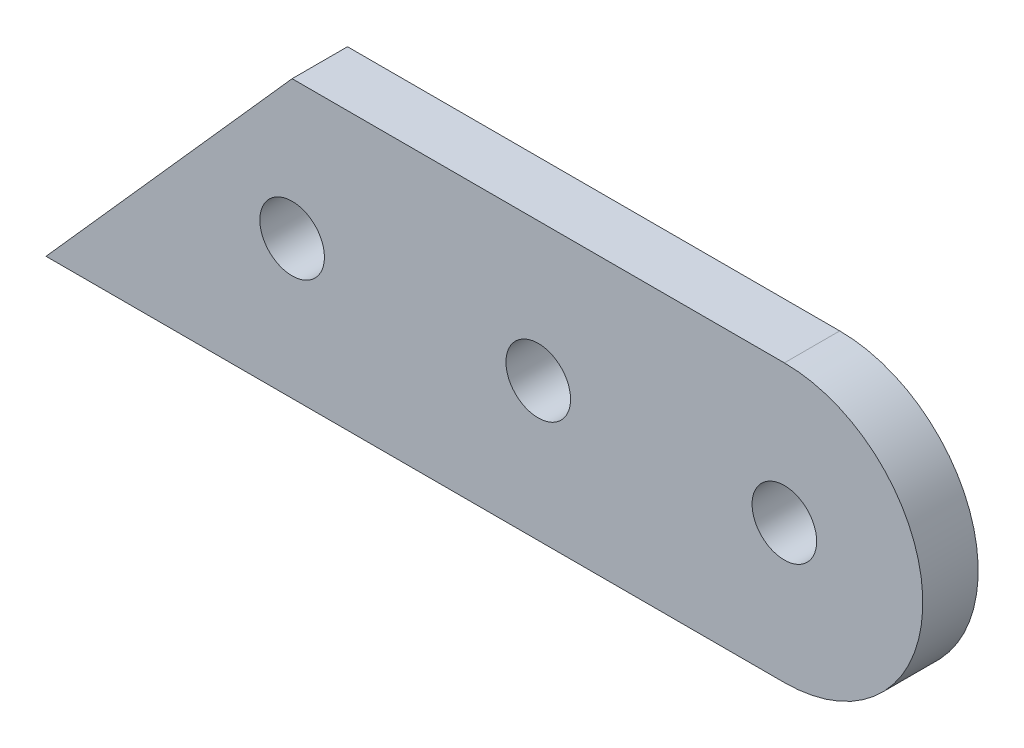
SolidWorks part; units mm, degrees
ref_plane "前基準面" through (0, 0, 0) normal (0, 0, 1) x (1, 0, 0)
ref_plane "上基準面" through (0, 0, 0) normal (0, 1, 0) x (1, 0, 0)
ref_plane "右基準面" through (0, 0, 0) normal (1, 0, 0) x (0, 0, -1)
sketch "草圖1" plane through (0, 0, 0) normal (0, 0, 1) x (1, 0, 0)
  line L0 (-20, 0) -> (-6.6667, 0) construction
  line L1 (-6.6667, 7.5) -> (20, 7.5)
  line L2 (-6.6667, 0) -> (6.6667, 0) construction
  line L3 (-20, -7.5) -> (20, -7.5)
  line L4 (6.6667, 0) -> (20, 0) construction
  line L5 (-20, 7.5) -> (20, -7.5) construction
  line L6 (-20, -7.5) -> (20, 7.5) construction
  line L7 (-20, 7.5) -> (-20, -7.5) construction
  line L8 (-20, -7.5) -> (-6.6667, 7.5)
  line L9 (-6.6667, 7.5) -> (-6.6667, 0) construction
  line L10 (-6.6667, 7.5) -> (-20, 7.5) construction
  arc A0 (20, 7.5) -> (20, -7.5) centre (20, 0) cw
  circle A3 centre (20, 0) radius 1.75
  circle A4 centre (-6.6667, 0) radius 1.75
  circle A5 centre (6.6667, 0) radius 1.75
  point P0 (0, 0)
  dimension "D3" = 3.5
  dimension "D1" = 15
  dimension "D2" = 40
extrude "伸長1" add sketch "草圖1" along normal blind 3
